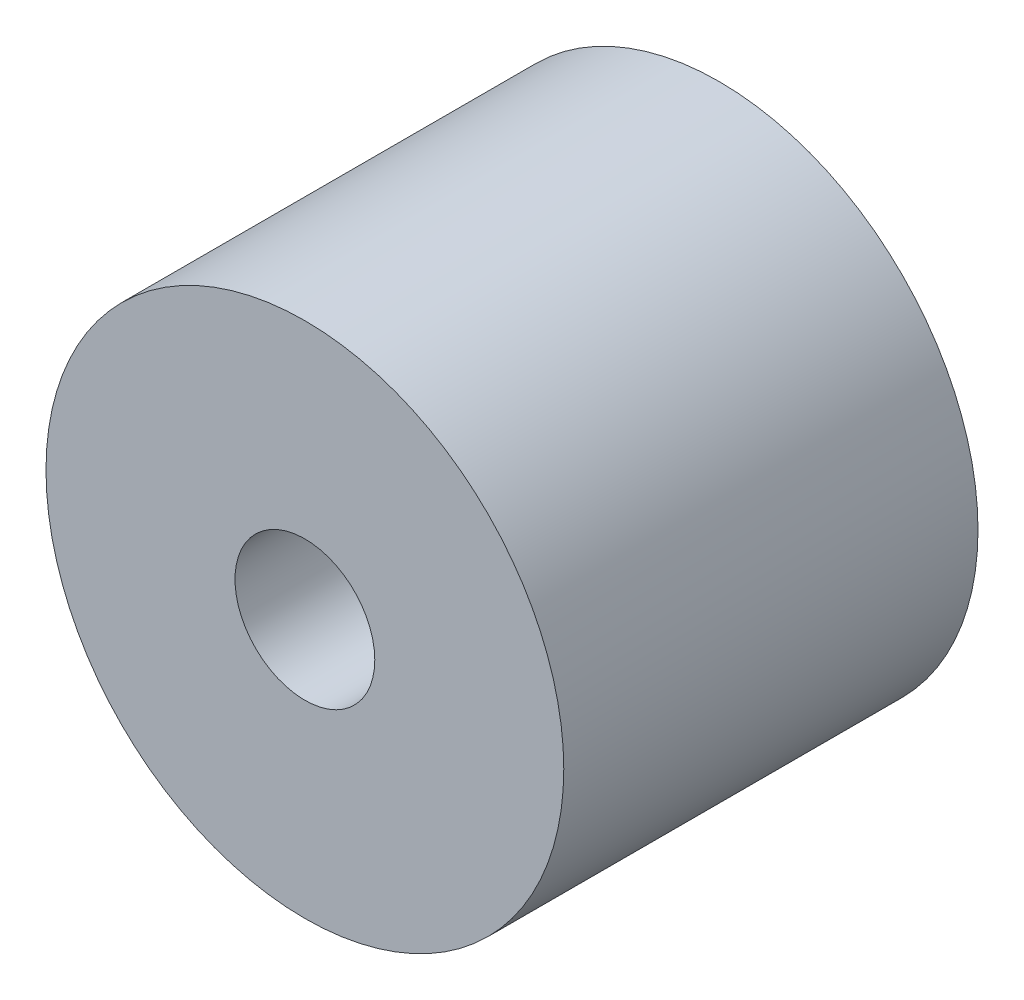
SolidWorks part; units mm, degrees
material "Brass"
ref_plane "Front Plane" through (0, 0, 0) normal (0, 0, 1) x (1, 0, 0)
ref_plane "Top Plane" through (0, 0, 0) normal (0, 1, 0) x (1, 0, 0)
ref_plane "Right Plane" through (0, 0, 0) normal (1, 0, 0) x (0, 0, -1)
sketch "Sketch1" plane through (0, 0, 0) normal (0, 0, 1) x (1, 0, 0)
  circle A0 centre (0, 0) radius 6.35
  dimension "D1" = 12.7
extrude "Boss-Extrude1" add sketch "Sketch1" along normal blind 10.16
hole_wizard "3/8 (0.135) Diameter Hole1" positions "Sketch2" profile "Sketch3" hole size "3/8" standard "ANSI Inch" end condition through all
sketch "Sketch2" plane through (0, 0, 10.16) normal (0, 0, 1) x (1, 0, 0)
  point P0 (0, 0)
sketch "Sketch3" plane through (0, 0, 10.16) normal (1, 0, 0) x (0, -1, 0)
  line L0 (0, 0) -> (0, 10.16)
  line L1 (0, 10.16) -> (1.7145, 10.16)
  line L2 (1.7145, 10.16) -> (1.7145, 0)
  line L5 (1.7145, 0) -> (0, 0)
  line L11 (0, -6.35) -> (0, 107.95) construction
  dimension "Thru Hole Dia." = 3.429
  dimension "Thru Hole Depth" = 10.16
